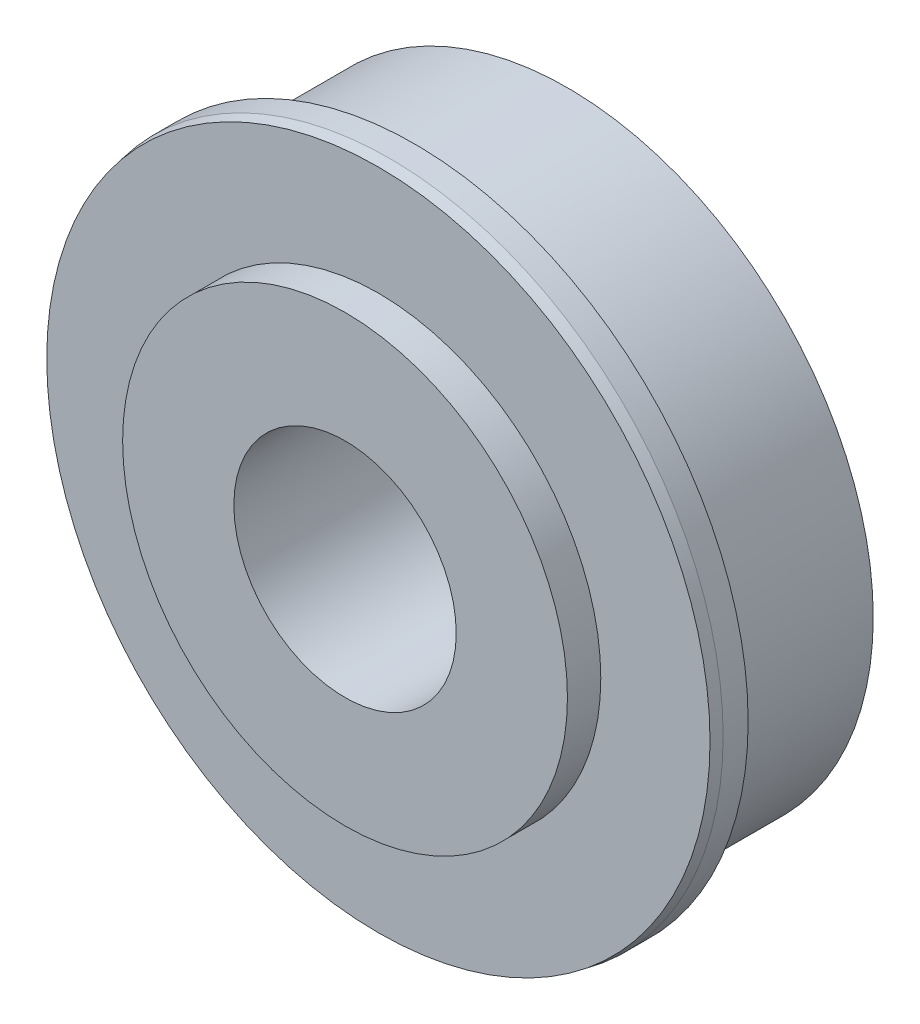
SolidWorks part; units mm, degrees
material "1023 Carbon Steel Sheet (SS)"
ref_plane "Front Plane" through (0, 0, 0) normal (1, 0, 0) x (0, 1, 0)
ref_plane "Top Plane" through (0, 0, 0) normal (0, 0, 1) x (0, 1, 0)
ref_plane "Right Plane" through (0, 0, 0) normal (0, 1, 0) x (-1, 0, 0)
sketch "Sketch1" plane through (0, 0, 0) normal (0, 1, 0) x (-1, 0, 0)
  line L0 (0, 114.8517) -> (0, -101.7673) construction
  line L1 (-17.4625, -6.35) -> (-17.4625, 1.7462)
  line L2 (-17.4625, 1.7462) -> (-17.3505, 2.3812)
  line L3 (-17.3505, 2.3812) -> (-19.05, 2.3812)
  line L4 (-19.05, 2.3812) -> (-19.05, 3.81)
  line L5 (-19.05, 3.81) -> (-18.938, 4.445)
  line L9 (-6.35, 6.35) -> (-6.35, -6.35)
  line L10 (-12.7, 6.35) -> (-6.35, 6.35)
  line L11 (-17.4625, -6.35) -> (-6.35, -6.35)
  line L12 (-17.4625, 1.7462) -> (-17.4625, 2.3812) construction
  line L13 (-18.938, 4.445) -> (-12.7, 4.445)
  line L14 (-12.7, 4.445) -> (-12.7, 6.35)
  line L15 (-18.938, 4.445) -> (-18.938, 3.81) construction
  line L16 (-18.938, 3.81) -> (-19.05, 3.81) construction
  line L17 (-6.35, 0) -> (0, 0) construction
  dimension "D1" = 12.7
  dimension "D2" = 34.925
  dimension "D3" = 10
  dimension "D4" = 38.1
  dimension "D5" = 12.7
  dimension "D6" = 3.9688
  dimension "D7" = 0.635
  dimension "D8" = 0.635
  dimension "D9" = 25.4
  dimension "D10" = 1.905
revolve "Revolve1" add sketch "Sketch1" angle 360 about L0
